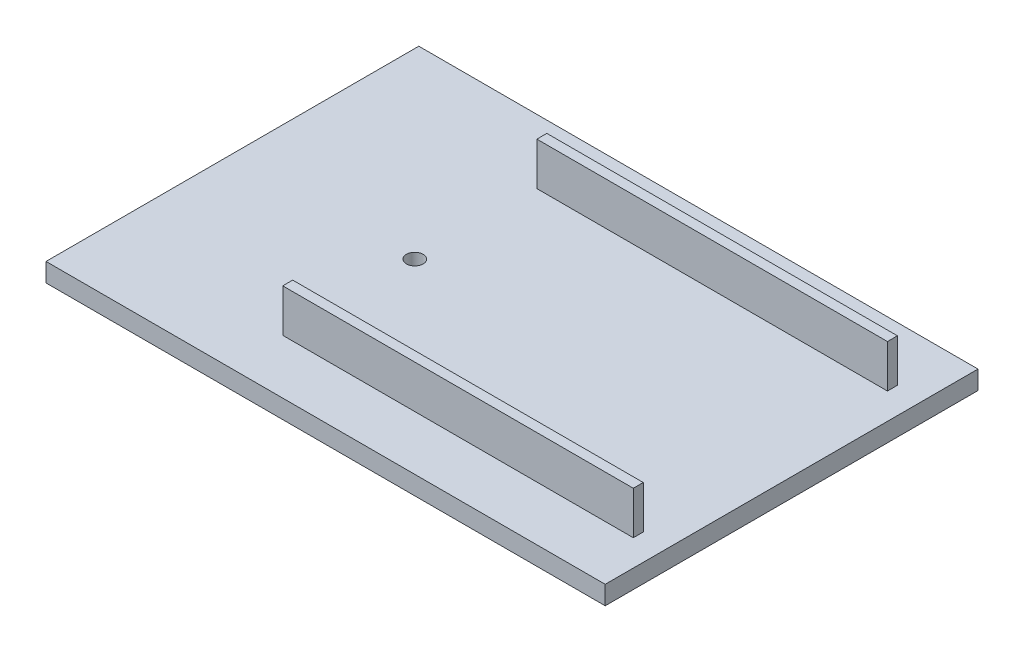
SolidWorks part; units mm, degrees
ref_plane "Front Plane" through (0, 0, 0) normal (0, 0, 1) x (1, 0, 0)
ref_plane "Top Plane" through (0, 0, 0) normal (0, 1, 0) x (1, 0, 0)
ref_plane "Right Plane" through (0, 0, 0) normal (1, 0, 0) x (0, 0, -1)
sketch "Sketch1" plane through (0, 0, 0) normal (0, 1, 0) x (1, 0, 0)
  line L1 (-150, 100) -> (150, 100)
  line L2 (-150, 100) -> (-150, -100)
  line L3 (-150, -100) -> (150, -100)
  line L4 (150, 100) -> (150, -100)
  line L5 (-150, 100) -> (150, -100) construction
  line L6 (-150, -100) -> (150, 100) construction
  point P0 (0, 0)
  dimension "D1" = 200
  dimension "D2" = 300
extrude "Boss-Extrude1" add sketch "Sketch1" along normal blind 10
sketch "Sketch2" plane through (0, 10, 0) normal (0, 1, 0) x (1, 0, 0)
  circle A0 centre (-52.1494, 0) radius 4.5
  dimension "D1" = 9
extrude "Cut-Extrude1" cut sketch "Sketch2" against normal blind 7 contours A0
sketch "Sketch3" plane through (0, 3, 0) normal (0, 1, 0) x (1, 0, 0)
  line L0 (-52.1494, 0) -> (-52.1494, 65.5) construction
  line L1 (-52.1494, 0) -> (61.4402, 0) construction
  line L2 (-52.1494, -70.8377) -> (135.9222, -70.8377)
  line L3 (-52.1494, 65.5) -> (135.9222, 65.5)
  line L4 (-52.1494, 65.5) -> (-52.1494, 70.8377)
  line L5 (-52.1494, 70.8377) -> (135.9222, 70.8377)
  line L6 (135.9222, 65.5) -> (135.9222, 70.8377)
  line L7 (135.9222, -65.5) -> (135.9222, -70.8377)
  line L8 (-52.1494, -65.5) -> (135.9222, -65.5)
  line L9 (-52.1494, -65.5) -> (-52.1494, -70.8377)
  dimension "D1" = 65.5
extrude "Boss-Extrude2" add sketch "Sketch3" along normal blind 30
